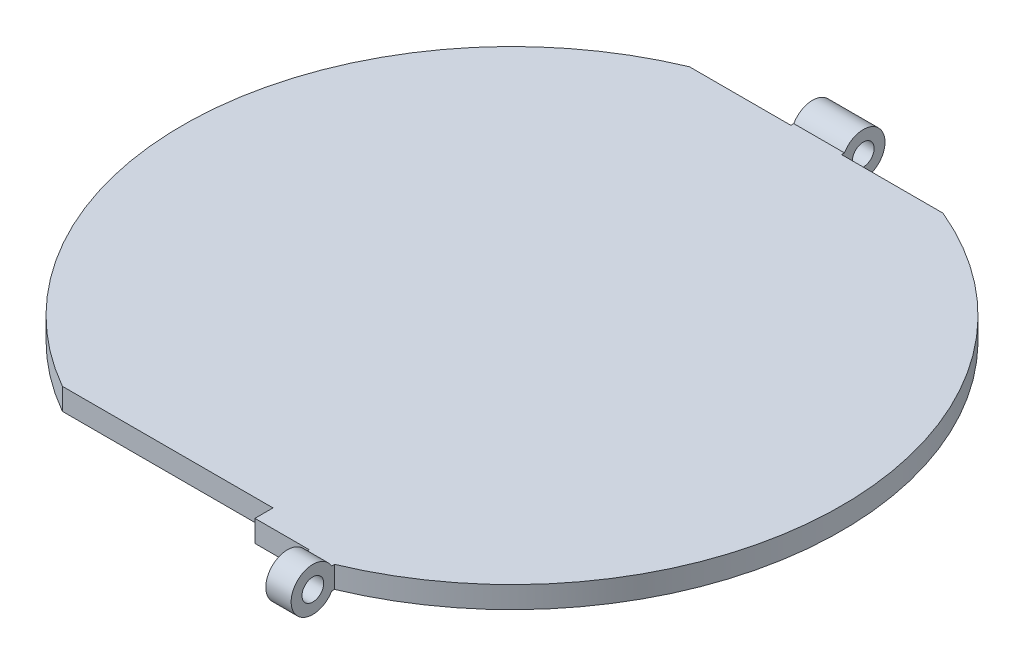
SolidWorks part; units mm, degrees
ref_plane "Front Plane" through (0, 0, 0) normal (0, 0, 1) x (1, 0, 0)
ref_plane "Top Plane" through (0, 0, 0) normal (0, 1, 0) x (1, 0, 0)
ref_plane "Right Plane" through (0, 0, 0) normal (1, 0, 0) x (0, 0, -1)
sketch "Sketch1" plane through (0, 0, 0) normal (0, 1, 0) x (1, 0, 0)
  line L0 (-17.5, -42) -> (17.5, -42)
  line L1 (0, 0) -> (36.3754, 0) construction
  line L2 (-17.5, 42) -> (17.5, 42)
  arc A0 (-17.5, 42) -> (-17.5, -42) centre (0, 0) ccw
  arc A1 (17.5, -42) -> (17.5, 42) centre (0, 0) ccw
  dimension "D1" = 91
  dimension "D2" = 42
  dimension "D3" = 42
extrude "Boss-Extrude1" add sketch "Sketch1" along normal blind 3
sketch "Sketch2" plane through (0, 0, 0) normal (1, 0, 0) x (0, 0, -1)
  line L0 (-43.0566, 1.5) -> (50.2125, 1.5) construction
  line L1 (-42, 3) -> (-42, 0) construction
  line L2 (-42, 0) -> (-42.4019, 0)
  line L3 (-42, 0) -> (42, 0) construction
  line L4 (-42, 0) -> (-42, 1.5)
  line L5 (-42, 1.5) -> (-42, 3)
  line L6 (-42, 3) -> (-42.4019, 3)
  line L7 (42, 3) -> (-42, 3) construction
  circle A0 centre (-45, 1.5) radius 1.5
  arc A1 (-42.4019, 3) -> (-42.4019, 0) centre (-45, 1.5) ccw
  point P4 (-42, 1.5)
  dimension "D1" = 6
  dimension "D2" = 3
extrude "Boss-Extrude2" add sketch "Sketch2" along normal blind 17.5 and the other way blind 10
mirror "Mirror1" about plane through (0, 0, 0) normal (0, 0, 1) of "Boss-Extrude2"
sketch "Sketch3" plane through (-10, 0, 0) normal (-1, 0, 0) x (0, 0, 1)
  line L0 (42, 0) -> (42, 3) construction
  line L1 (42, 6.5) -> (50, 6.5)
  line L2 (42, 6.5) -> (42, -2.5)
  line L3 (42, -2.5) -> (50, -2.5)
  line L4 (50, 6.5) -> (50, -2.5)
  circle A0 centre (45, 1.5) radius 1.5 construction
  dimension "D1" = 9
  dimension "D2" = 8
  dimension "D3" = 5
extrude "Cut-Extrude1" cut sketch "Sketch3" against normal blind 24
sketch "Sketch4" plane through (-10, 0, 0) normal (-1, 0, 0) x (0, 0, 1)
  line L5 (-42, 0) -> (-42, 3) construction
  line L6 (-42, -2.5) -> (-50, -2.5)
  line L7 (-42, -2.5) -> (-42, 6.5)
  line L8 (-42, 6.5) -> (-50, 6.5)
  line L10 (-50, 6.5) -> (-50, -2.5)
  circle A0 centre (-45, 1.5) radius 1.5 construction
  dimension "D1" = 8
  dimension "D2" = 9
  dimension "D3" = 5
extrude "Cut-Extrude2" cut sketch "Sketch4" against normal blind 6.5
ref_plane "Plane1" through (6.5, 0, 0) normal (-1, 0, 0) x (0, 0, 1)
sketch "Sketch5" plane through (17.5, 0, 0) normal (1, 0, 0) x (0, 0, -1)
  line L0 (42, 3) -> (42, 0) construction
  line L1 (42, 5.0896) -> (49, 5.0896)
  line L2 (42, 5.0896) -> (42, -1.9104)
  line L3 (42, -1.9104) -> (49, -1.9104)
  line L4 (49, 5.0896) -> (49, -1.9104)
  arc A0 (42.4019, 0) -> (42.4019, 3) centre (45, 1.5) ccw construction
  dimension "D1" = 7
  dimension "D2" = 7
  dimension "D3" = 3.5896
extrude "Cut-Extrude3" cut sketch "Sketch5" against normal blind 14
sketch "Sketch6" plane through (6.5, 0, 0) normal (-1, 0, 0) x (0, 0, 1)
  line L1 (39.5, 7.5) -> (50.5, 7.5)
  line L2 (39.5, 7.5) -> (39.5, -4.5)
  line L3 (39.5, -4.5) -> (50.5, -4.5)
  line L4 (50.5, 7.5) -> (50.5, -4.5)
  point P4 (45, 1.5)
  point P5 (0, 0)
  point P7 (45, 7.5)
  point P8 (50.5, 1.5)
  dimension "D1" = 11
  dimension "D2" = 12
extrude "Cut-Extrude4" cut sketch "Sketch6" along normal up to surface up to face at (-31.5, 1.5, 0)
